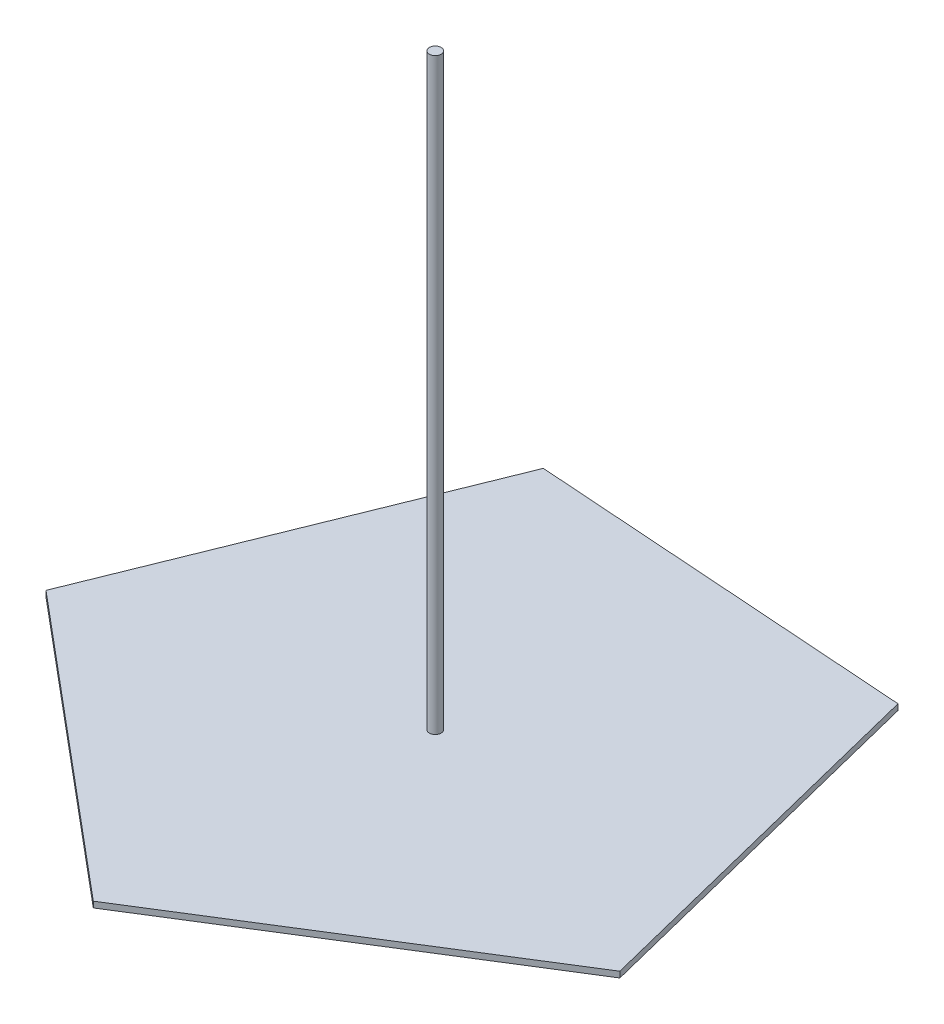
SolidWorks part; units mm, degrees
ref_plane "Front Plane" through (0, 0, 0) normal (0, 0, 1) x (1, 0, 0)
ref_plane "Top Plane" through (0, 0, 0) normal (0, 1, 0) x (1, 0, 0)
ref_plane "Right Plane" through (0, 0, 0) normal (1, 0, 0) x (0, 0, -1)
sketch "Sketch3" plane through (0, 0, 0) normal (0, 1, 0) x (1, 0, 0)
  line L1 (90.2121, 107.5924) -> (-74.4494, 119.0446)
  line L2 (-74.4494, 119.0446) -> (-136.2243, -34.0187)
  line L3 (-136.2243, -34.0187) -> (-9.7419, -140.0694)
  line L4 (-9.7419, -140.0694) -> (130.2035, -52.5489)
  line L5 (130.2035, -52.5489) -> (90.2121, 107.5924)
  circle A0 centre (0, 0) radius 113.5923 construction
  dimension "D1" = 254
extrude "Boss-Extrude3" add sketch "Sketch3" along normal blind 2.54
sketch "Sketch4" plane through (0, 2.54, 0) normal (0, 1, 0) x (1, 0, 0)
  circle A0 centre (0, -2.0795) radius 2.54
extrude "Boss-Extrude4" add sketch "Sketch4" along normal blind 254
